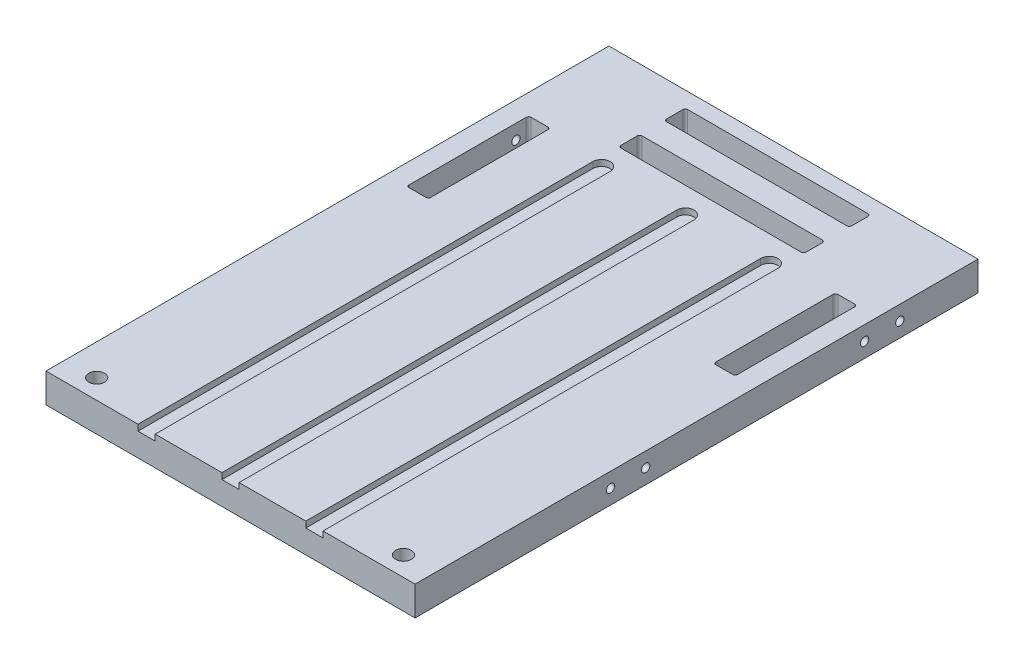
SolidWorks part; units mm, degrees
material "6061-T6 (SS)"
ref_plane "Front Plane" through (0, 0, 0) normal (0, 0, 1) x (1, 0, 0)
ref_plane "Top Plane" through (0, 0, 0) normal (0, 1, 0) x (1, 0, 0)
ref_plane "Right Plane" through (0, 0, 0) normal (1, 0, 0) x (0, 0, -1)
sketch "Sketch1" plane through (0, 0, 0) normal (0, 1, 0) x (1, 0, 0)
  line L0 (0, 91.44) -> (0, -91.44) construction
  line L1 (-59.944, -91.44) -> (59.944, -91.44)
  line L2 (-59.944, -91.44) -> (-59.944, 91.44)
  line L3 (-59.944, 91.44) -> (59.944, 91.44)
  line L4 (59.944, -91.44) -> (59.944, 91.44)
  line L5 (-59.944, -91.44) -> (59.944, 91.44) construction
  line L6 (-59.944, 91.44) -> (59.944, -91.44) construction
  line L7 (-29.2671, 79.502) -> (29.2671, 79.502)
  line L8 (-30.0609, 80.2957) -> (-30.0609, 85.5662)
  line L9 (-29.2671, 86.36) -> (29.2671, 86.36)
  line L10 (30.0609, 80.2957) -> (30.0609, 85.5662)
  line L11 (-30.0609, 79.502) -> (30.0609, 86.36) construction
  line L12 (-30.0609, 86.36) -> (30.0609, 79.502) construction
  line L13 (-29.2672, 64.6811) -> (29.2671, 64.6811)
  line L14 (-30.0609, 65.4748) -> (-30.0609, 70.7453)
  line L15 (-29.2671, 71.5391) -> (29.2671, 71.5391)
  line L16 (30.0609, 65.4748) -> (30.0609, 70.7453)
  line L17 (-30.0609, 64.6811) -> (30.0609, 71.5391) construction
  line L18 (-30.0609, 71.5391) -> (30.0609, 64.6811) construction
  line L19 (-52.5462, 19.1262) -> (-47.1106, 19.1262)
  line L20 (-53.34, 19.92) -> (-53.34, 57.9564)
  line L21 (-52.5462, 58.7502) -> (-47.1106, 58.7502)
  line L22 (-46.3169, 19.92) -> (-46.3169, 57.9564)
  line L23 (-53.34, 19.1262) -> (-46.3169, 58.7502) construction
  line L24 (-53.34, 58.7502) -> (-46.3169, 19.1262) construction
  line L25 (53.34, 58.7502) -> (46.3169, 19.1262) construction
  line L26 (53.34, 19.1262) -> (46.3169, 58.7502) construction
  line L27 (46.3169, 19.92) -> (46.3169, 57.9564)
  line L28 (52.5463, 58.7502) -> (47.1107, 58.7502)
  line L29 (53.34, 19.92) -> (53.34, 57.9564)
  line L30 (52.5463, 19.1262) -> (47.1107, 19.1262)
  arc A0 (-29.2672, 64.6811) -> (-30.0609, 65.4748) centre (-29.2672, 65.4748) cw
  arc A1 (-30.0609, 70.7453) -> (-29.2671, 71.5391) centre (-29.2672, 70.7454) cw
  arc A2 (29.2671, 64.6811) -> (30.0609, 65.4748) centre (29.2671, 65.4748) ccw
  arc A3 (29.2671, 71.5391) -> (30.0609, 70.7453) centre (29.2671, 70.7454) cw
  arc A4 (29.2671, 79.502) -> (30.0609, 80.2957) centre (29.2672, 80.2957) ccw
  arc A5 (29.2671, 86.36) -> (30.0609, 85.5662) centre (29.2672, 85.5662) cw
  arc A6 (-29.2671, 79.502) -> (-30.0609, 80.2957) centre (-29.2671, 80.2957) cw
  arc A7 (-30.0609, 85.5662) -> (-29.2671, 86.36) centre (-29.2671, 85.5662) cw
  arc A8 (-52.5462, 19.1262) -> (-53.34, 19.92) centre (-52.5462, 19.9199) cw
  arc A9 (-47.1106, 19.1262) -> (-46.3169, 19.92) centre (-47.1106, 19.9199) ccw
  arc A10 (-47.1106, 58.7502) -> (-46.3169, 57.9564) centre (-47.1106, 57.9564) cw
  arc A11 (-53.34, 57.9564) -> (-52.5462, 58.7502) centre (-52.5462, 57.9564) cw
  arc A12 (53.34, 57.9564) -> (52.5463, 58.7502) centre (52.5463, 57.9564) ccw
  arc A13 (47.1107, 58.7502) -> (46.3169, 57.9564) centre (47.1107, 57.9564) ccw
  arc A14 (47.1107, 19.1262) -> (46.3169, 19.92) centre (47.1107, 19.9199) cw
  arc A15 (52.5463, 19.1262) -> (53.34, 19.92) centre (52.5463, 19.9199) ccw
  point P0 (0, 0)
  point P6 (0, 82.931)
  point P11 (0, 68.1101)
  point P40 (-49.8284, 38.9382)
  point P77 (49.8285, 38.9382)
  dimension "D11" = 0.7937
  dimension "D16" = 0.7937
  dimension "D1" = 119.888
  dimension "D2" = 182.88
  dimension "D3" = 5.08
  dimension "D4" = 6.858
  dimension "D5" = 60.1218
  dimension "D6" = 0
  dimension "D7" = 60.1218
  dimension "D8" = 0
  dimension "D9" = 7.9629
  dimension "D10" = 6.858
  dimension "D12" = 6.604
  dimension "D13" = 32.6898
  dimension "D14" = 7.0231
  dimension "D15" = 39.624
extrude "Boss-Extrude1" add sketch "Sketch1" along normal blind 9.525
sketch "Sketch2" plane through (0, 9.525, 0) normal (0, 1, 0) x (1, 0, 0)
  line L0 (-59.944, -91.44) -> (59.944, -91.44) construction
  line L1 (-52.5462, 19.1262) -> (-47.1106, 19.1262) construction
  line L2 (0, 91.44) -> (0, -91.44) construction
  line L3 (59.944, 91.44) -> (-59.944, 91.44) construction
  point P0 (-49.8284, -85.09)
  point P5 (-49.8284, 19.1262)
  point P11 (49.8285, -85.09)
  dimension "D1" = 6.35
  dimension "D2" = 0
hole_wizard "1/4-20 Tapped Hole1" positions "Sketch2" profile "Sketch3" tap size "1/4-20" standard "ANSI Inch" end condition through all
sketch "Sketch3" plane through (-49.8284, 9.525, 85.09) normal (1, 0, 0) x (0, 0, 1)
  line L0 (0, 0) -> (0, 9.525)
  line L1 (0, 9.525) -> (2.5527, 9.525)
  line L2 (2.5527, 9.525) -> (2.5527, 0)
  line L5 (2.5527, 0) -> (0, 0)
  line L11 (0, -6.35) -> (0, 107.95) construction
  dimension "Thru Tap Drill Dia." = 5.1054
  dimension "Thru Tap Drill Depth" = 9.525
cosmetic thread "Hole Thread1" parameters "D2"=6.35
cosmetic thread "Hole Thread2" parameters "D2"=6.35
sketch "Sketch4" plane through (0, 9.525, 0) normal (0, 1, 0) x (1, 0, 0)
  line L0 (0, 64.6811) -> (0, -91.44) construction
  line L3 (0, 56.3372) -> (-30.0482, 56.3372) construction
  line L4 (-30.0482, -91.44) -> (-24.4602, -91.44)
  line L5 (-29.2672, 64.6811) -> (29.2671, 64.6811) construction
  line L7 (-2.794, 56.3372) -> (-2.794, -91.44)
  line L9 (-24.4602, 56.3372) -> (-24.4602, -91.44)
  line L11 (-30.0482, 56.3372) -> (-30.0482, -91.44)
  line L12 (-2.794, -91.44) -> (2.794, -91.44)
  line L13 (30.0482, 56.3372) -> (30.0482, -91.44)
  line L15 (24.4602, 56.3372) -> (24.4602, -91.44)
  line L16 (2.794, 56.3372) -> (2.794, -91.44)
  line L17 (30.0482, -91.44) -> (24.4602, -91.44)
  line L18 (0, 56.3372) -> (30.0482, 56.3372) construction
  arc A0 (-30.0482, 56.3372) -> (-24.4602, 56.3372) centre (-27.2542, 56.3372) cw
  arc A1 (-2.794, 56.3372) -> (2.794, 56.3372) centre (0, 56.3372) cw
  arc A2 (24.4602, 56.3372) -> (30.0482, 56.3372) centre (27.2542, 56.3372) cw
  point P22 (0, 58.7502)
  dimension "D2" = 2.794
  dimension "D1" = 27.2542
  dimension "D3" = 2.794
extrude "Cut-Extrude1" cut sketch "Sketch4" against normal blind 1.9685
sketch "Sketch5" plane through (0, 0, 0) normal (0, -1, 0) x (1, 0, 0)
  line L0 (0, -79.502) -> (0, -71.5391) construction
  line L1 (29.2671, -71.5391) -> (-29.2671, -71.5391) construction
  line L2 (-29.2671, -79.502) -> (29.2671, -79.502) construction
  line L3 (-29.2671, -79.502) -> (29.2671, -79.502) construction
  line L4 (29.2671, -71.5391) -> (-29.2671, -71.5391) construction
  line L5 (0, -75.5205) -> (-40.005, -75.5205) construction
  line L6 (0, -75.5205) -> (40.005, -75.5205) construction
  line L7 (-40.005, -75.5205) -> (40.005, -75.5205) construction
  line L8 (-40.005, -73.1076) -> (40.005, -73.1076)
  line L9 (-40.005, -77.9335) -> (40.005, -77.9335)
  line L10 (0, -64.6811) -> (0, -56.7182) construction
  line L11 (-29.2672, -64.6811) -> (29.2671, -64.6811) construction
  line L12 (-40.005, -60.6996) -> (40.005, -60.6996) construction
  line L13 (-40.005, -58.2867) -> (40.005, -58.2867)
  line L14 (-40.005, -63.1126) -> (40.005, -63.1126)
  arc A0 (-40.005, -73.1076) -> (-40.005, -77.9335) centre (-40.005, -75.5205) ccw
  arc A1 (40.005, -77.9335) -> (40.005, -73.1076) centre (40.005, -75.5205) ccw
  arc A2 (-40.005, -58.2867) -> (-40.005, -63.1126) centre (-40.005, -60.6996) ccw
  arc A3 (40.005, -63.1126) -> (40.005, -58.2867) centre (40.005, -60.6996) ccw
  point P8 (0, -75.5205)
  point P20 (0, -60.6996)
  dimension "D1" = 40.005
  dimension "D2" = 40.005
  dimension "D3" = 4.826
  dimension "D4" = 7.9629
extrude "Cut-Extrude2" cut sketch "Sketch5" against normal blind 1.9685
sketch "Sketch6" plane through (-59.944, 0, 0) normal (-1, 0, 0) x (0, 0, 1)
  line L0 (-91.44, 4.7625) -> (91.44, 4.7625) construction
  line L1 (-91.44, 9.525) -> (-91.44, 0) construction
  line L2 (91.44, 9.525) -> (91.44, 0) construction
  point P6 (-66.04, 4.7625)
  point P7 (-54.61, 4.7625)
  point P8 (16.51, 4.7625)
  point P9 (27.94, 4.7625)
  dimension "D1" = 25.4
  dimension "D2" = 11.43
  dimension "D3" = 11.43
  dimension "D4" = 107.95
hole_wizard "#6-32 Tapped Hole1" positions "Sketch6" profile "Sketch7" tap size "#6-32" standard "ANSI Inch"
sketch "Sketch7" plane through (-59.944, 4.7625, 27.94) normal (0, 1, 0) x (0, 0, 1)
  line L0 (0, 0) -> (0, 13.5127)
  line L1 (0, 13.5127) -> (1.3525, 12.7)
  line L2 (1.3525, 12.7) -> (1.3525, 0)
  line L5 (1.3525, 0) -> (0, 0)
  line L10 (0, 13.5127) -> (-1.3526, 12.7) construction
  line L11 (0, -6.35) -> (0, 107.95) construction
  dimension "Tap Drill Dia." = 2.7051
  dimension "Tap Drill Depth" = 12.7
  dimension "Drill Angle" = 118
cosmetic thread "Hole Thread3" parameters "D1"=7.112, "D2"=3.5052
cosmetic thread "Hole Thread4" parameters "D1"=7.112, "D2"=3.5052
cosmetic thread "Hole Thread5" parameters "D1"=7.112, "D2"=3.5052
cosmetic thread "Hole Thread6" parameters "D1"=7.112, "D2"=3.5052
mirror "Mirror1" about plane through (0, 0, 0) normal (1, 0, 0) of "#6-32 Tapped Hole1"
cosmetic thread "Hole Thread7" parameters "D1"=7.112, "D2"=3.5052
cosmetic thread "Hole Thread8" parameters "D1"=7.112, "D2"=3.5052
cosmetic thread "Hole Thread9" parameters "D1"=7.112, "D2"=3.5052
cosmetic thread "Hole Thread10" parameters "D1"=7.112, "D2"=3.5052
equation "\"D7@Sketch1\"=\"D5@Sketch1\""
equation "\"D1@Sketch5\"=3.15/2"
equation "\"D2@Sketch5\"=3.15/2"
